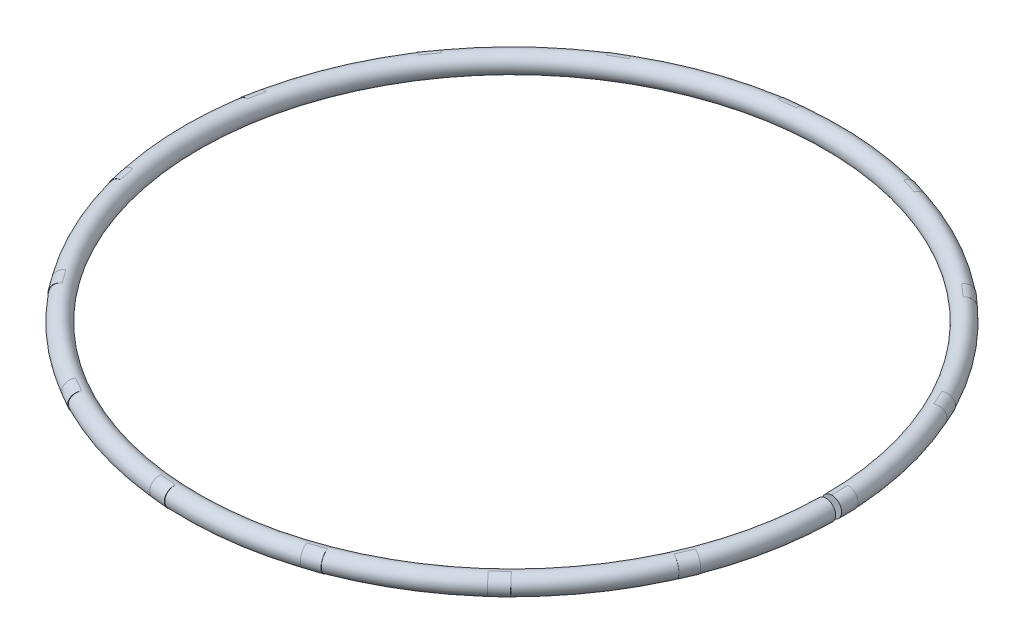
SolidWorks part; units mm, degrees
material "AISI 304"
ref_plane "Plano frontal" through (0, 0, 0) normal (0, 0, 1) x (1, 0, 0)
ref_plane "Plano superior" through (0, 0, 0) normal (0, 1, 0) x (1, 0, 0)
ref_plane "Plano direito" through (0, 0, 0) normal (1, 0, 0) x (0, 0, -1)
sketch "Esboço1" plane through (0, 0, 0) normal (0, 0, 1) x (1, 0, 0)
  line L0 (0, 0) -> (19.5, 0) construction
  line L1 (0, 0) -> (0, 1) construction
  circle A0 centre (19.5, 0) radius 0.6
  dimension "D2" = 1.2
  dimension "D1" = 19.5
  dimension "D3" = 1
revolve "Revolução1" add sketch "Esboço1" angle 359 about L1
sketch "Esboço2" plane through (0, 0, 0) normal (0, 0, 1) x (1, 0, 0)
  line L0 (0, 0) -> (19.5, 0) construction
  line L1 (0, 0) -> (0, 4) construction
  circle A0 centre (19.5, 0) radius 0.6
  point P4 (19.5, 0)
  dimension "D1" = 1.2
  dimension "D2" = 19.5
  dimension "D3" = 4
extrude "Ressalto-extrusão1" add sketch "Esboço2" against normal blind 1 separate body
sketch "Esboço4" plane through (0, 0, 0) normal (0, 0, 1) x (1, 0, 0)
  line L0 (0, 0) -> (0, 6.0367) construction
pattern_circular "PadrãoCircular4" count 15 over 360 about axis through (0, 0, 0) along (0, 1, 0) of bodies 102
sketch "Esboço5" plane through (0, 0, 0) normal (0, 0, 1) x (1, 0, 0)
  line L0 (18.9, 0) -> (20.1, 0) construction
  circle A0 centre (19.5, 0) radius 0.6 construction
  point P5 (19.5, 0)
